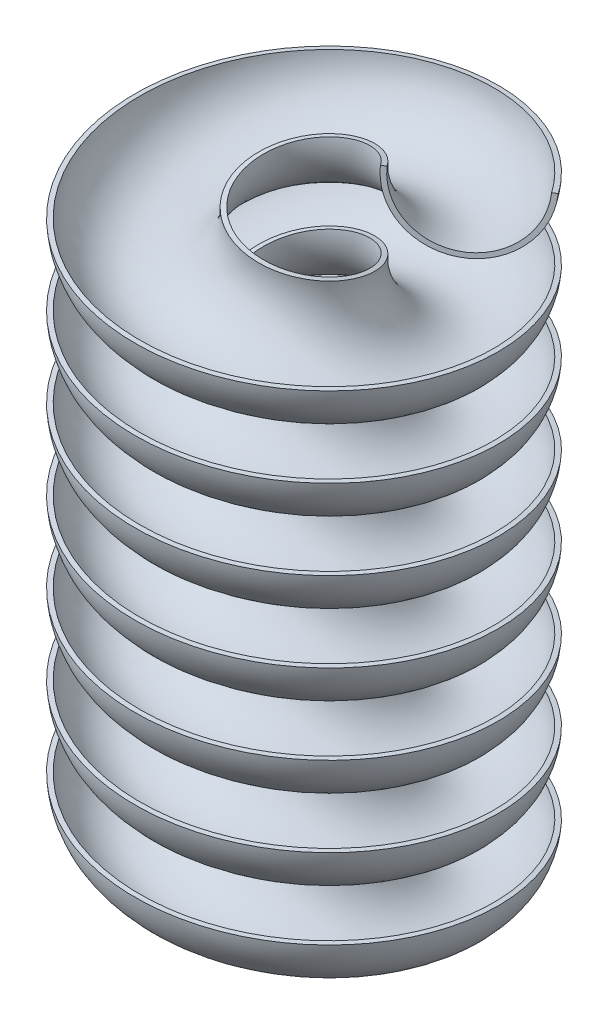
SolidWorks part; units mm, degrees
ref_plane "Front Plane" through (0, 0, 0) normal (0, 0, 1) x (1, 0, 0)
ref_plane "Top Plane" through (0, 0, 0) normal (0, 1, 0) x (1, 0, 0)
ref_plane "Right Plane" through (0, 0, 0) normal (1, 0, 0) x (0, 0, -1)
sketch "Sketch1" plane through (0, 0, 0) normal (0, 1, 0) x (1, 0, 0)
  circle A0 centre (0, 0) radius 500
  dimension "D1" = 1000
curve "Helix/Spiral1" pitch 337.8378 height 2500 turns 7.4
ref_plane "Plane2" through (404.5085, 2500, -293.8926) normal (0.5844, 0.1069, 0.8044) x (0.8115, -0.077, -0.5793)
sketch "Sketch3" plane through (404.5085, 2500, -293.8926) normal (0.5844, 0.1069, 0.8044) x (0.8115, -0.077, -0.5793)
  line L0 (-250, 0) -> (-270, 0)
  line L1 (250, 0) -> (270, 0)
  arc A0 (-250, 0) -> (250, 0) centre (0, 0) ccw
  arc A1 (-270, 0) -> (270, 0) centre (0, 0) ccw
  circle A2 centre (0, 0) radius 270 construction
  circle A3 centre (0, 0) radius 250 construction
  dimension "D2" = 250
  dimension "D1" = 20
sweep "Sweep5" add profiles "Sketch3" path "Helix/Spiral1"
